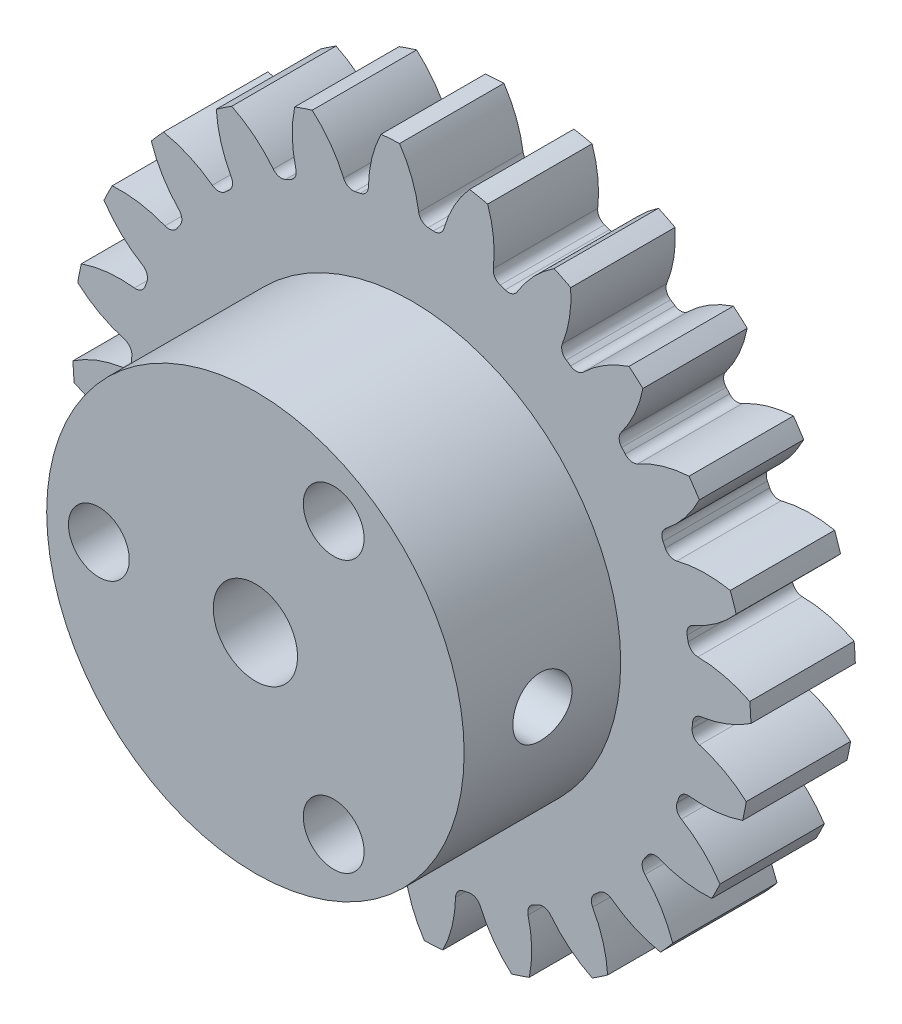
SolidWorks part; units mm, degrees
ref_plane "Front" through (0, 0, 0) normal (0, 0, 1) x (1, 0, 0)
ref_plane "Top" through (0, 0, 0) normal (0, 1, 0) x (1, 0, 0)
ref_plane "Right" through (0, 0, 0) normal (1, 0, 0) x (0, 0, -1)
sketch "Sketch3" plane through (0, 0, 0) normal (0, 0, 1) x (1, 0, 0)
  circle A0 centre (0, 0) radius 20.6375
  dimension "od" = 41.275
extrude "gearBody" add sketch "Sketch3" along normal blind 6.35
sketch "Sketch2" plane through (0, 0, 0) normal (0, 0, 1) x (1, 0, 0)
  line L0 (0, 0) -> (16.5385, 6.8505) construction
  line L1 (22.0347, -5.709) -> (0, 0) construction
  line L2 (0, 0) -> (36.3143, 0) construction
  line L3 (19.05, -0.043) -> (18.8852, -2.5004) construction
  line L5 (18.9676, -1.2717) -> (0, 0) construction
  line L7 (0, 0) -> (17.9011, 0) construction
  arc A0 (17.8975, -0.3593) -> (17.7853, -2.0332) centre (0, 0) ccw construction
  arc A1 (20.6236, 0.7563) -> (20.3381, -3.5027) centre (0, 0) ccw construction
  arc A2 (19.05, -0.043) -> (18.8852, -2.5004) centre (0, 0) ccw construction
  arc A3 (17.0444, -1.304) -> (17.0659, -0.983) centre (0, 0) ccw
  arc A4 (22.0347, -5.709) -> (17.4884, -1.9416) centre (15.476, -8.9969) ccw
  arc A5 (22.0347, -5.709) -> (22.5996, 2.7164) centre (0, 0) ccw
  arc A6 (22.5996, 2.7164) -> (17.5911, -0.4103) centre (16.5385, 6.8505) cw
  arc A7 (17.0659, -0.983) -> (17.5911, -0.4103) centre (17.6793, -1.0183) cw
  arc A8 (17.4884, -1.9416) -> (17.0444, -1.304) centre (17.657, -1.3509) cw
  point P6 (22.5996, 2.7164)
  point P22 (22.0347, -5.709)
  dimension "baseDia" = 35.8023
  dimension "od" = 41.275
  dimension "pd" = 38.1
  dimension "rd" = 34.1884
  dimension "rFillet" = 0.6144
  dimension "pointX" = 22.5996
  dimension "pointY" = 2.7164
  dimension "CTT" = 2.4574
  dimension "flankCenterAngle" = 22.5
extrude "toothCut" cut sketch "Sketch2" along normal through all
pattern_circular "CirPattern1" count 24 over 360 about axis through (0, 0, 0) along (0, 0, 1) of "toothCut"
sketch "hub1Dia" plane through (0, 0, 0) normal (0, 0, -1) x (-1, 0, 0)
  circle A0 centre (0, 0) radius 12.7
  dimension "hub1Dia" = 25.4
sketch "hub2Dia" plane through (0, 0, 6.35) normal (0, 0, 1) x (1, 0, 0)
  circle A0 centre (0, 0) radius 12.7
  dimension "hub2dia" = 25.4
sketch "boreDia" plane through (0, 0, 0) normal (0, 0, 1) x (1, 0, 0)
  circle A0 centre (0, 0) radius 6.35
  dimension "boreDia" = 12.7
extrude "Boss-Extrude1" add sketch "hub2Dia" along normal blind 9.525
sketch "Sketch4" plane through (0, 0, 0) normal (0, 0, -1) x (-1, 0, 0)
  circle A0 centre (9.525, 0) radius 1.85
  circle A1 centre (-4.7625, -8.2489) radius 1.85
  circle A2 centre (-4.7625, 8.2489) radius 1.85
  point P9 (0, 0)
  dimension "D2" = 3.7
  dimension "D1" = 9.525
  dimension "D3" = 3
extrude "Cut-Extrude1" cut sketch "Sketch4" against normal through all
sketch "Sketch5" plane through (0, 0, 0) normal (0, 0, -1) x (-1, 0, 0)
  circle A0 centre (0, 0) radius 2.5635
  dimension "D1" = 5.127
extrude "Cut-Extrude2" cut sketch "Sketch5" against normal through all
sketch "Sketch6" plane through (0, 0, 0) normal (1, 0, 0) x (0, 0, -1)
  line L0 (-15.875, 12.7) -> (-15.875, -12.7) construction
  circle A0 centre (-11.1125, 0) radius 1.8
  dimension "D2" = 3.6
  dimension "D1" = 4.7625
extrude "Cut-Extrude3" cut sketch "Sketch6" along normal through all
equation "\"D2@Sketch4\"=3.7mm"
equation "\"D1@Sketch5\"=\"tightTol\" + 5mm"
equation "\"tightTol\" = 0.005in"
equation "\"normTol\"= 0.01in"
equation "\"looseTol\"= 0.02in"
equation "\"D2@Sketch6\"=3.6mm"
